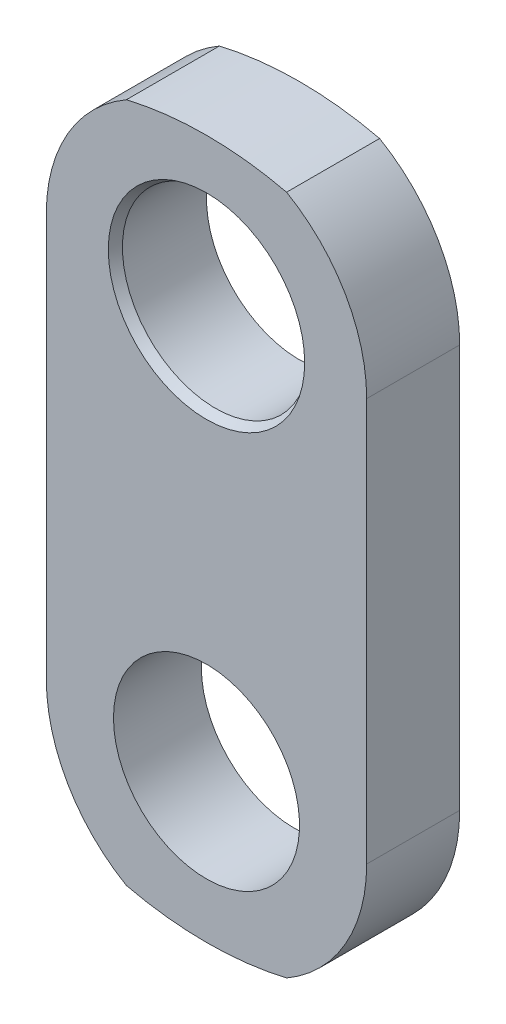
SolidWorks part; units mm, degrees
ref_plane "Спереди" through (0, 0, 0) normal (0, 0, 1) x (1, 0, 0)
ref_plane "Сверху" through (0, 0, 0) normal (0, 1, 0) x (1, 0, 0)
ref_plane "Справа" through (0, 0, 0) normal (1, 0, 0) x (0, 0, -1)
sketch "Эскиз1" plane through (0, 0, 0) normal (0, 0, 1) x (1, 0, 0)
  line L0 (-31, 39) -> (-31, -39)
  line L2 (31, 39) -> (31, -39)
  circle A0 centre (0, 39) radius 18
  arc A1 (31, 39) -> (15.5, 65.8468) centre (0, 39) ccw
  arc A2 (-15.5, -65.8468) -> (-31, -39) centre (0, -39) cw
  arc A3 (15.5, -65.8468) -> (-15.5, -65.8468) centre (0, 0) cw
  arc A4 (-15.5, 65.8468) -> (-31, 39) centre (0, 39) ccw
  arc A5 (15.5, 65.8468) -> (-15.5, 65.8468) centre (0, 0) ccw
  circle A6 centre (0, -39) radius 18
  arc A7 (31, -39) -> (15.5, -65.8468) centre (0, -39) cw
  point P6 (-31, 0)
  point P11 (31, 0)
  point P12 (-31, 0)
  point P18 (31, 0)
  dimension "D1" = 36
  dimension "D2" = 39
  dimension "D4" = 39
  dimension "D5" = 39
  dimension "D6" = 67.6465
  dimension "D3" = 31
extrude "Бобышка-Вытянуть1" add sketch "Эскиз1" along normal blind 18
chamfer "Фаска1" distance 1 angle 60 1 edges at (18, 39, 18)
chamfer "Фаска2" distance 1 angle 60 1 edges at (-18, -39, 0)
